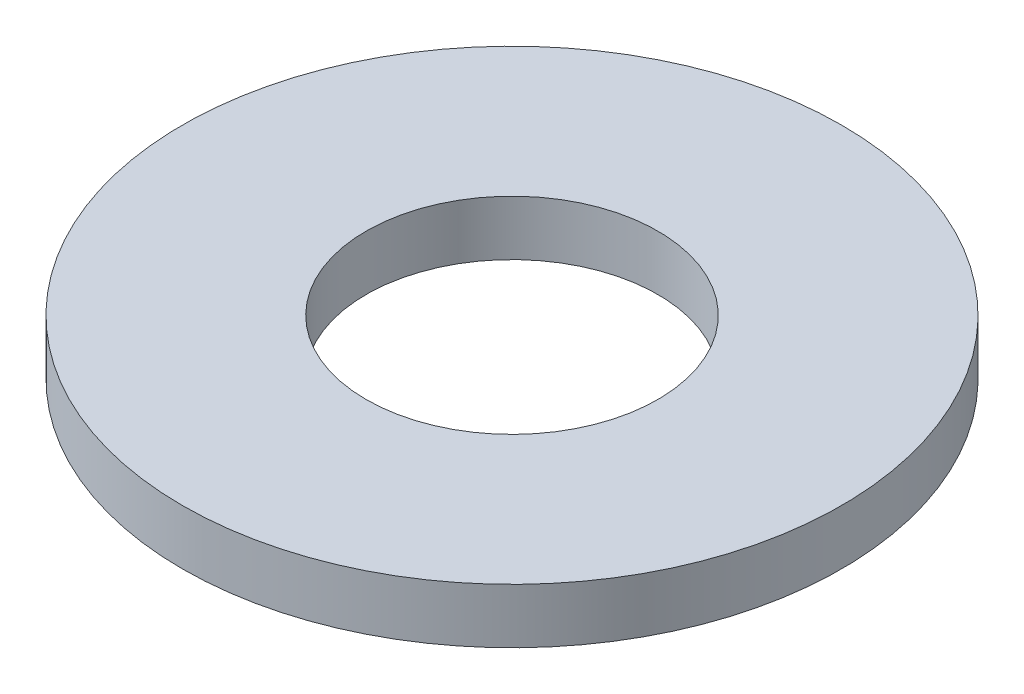
SolidWorks part; units mm, degrees
ref_plane "Front Plane" through (0, 0, 0) normal (0, 0, 1) x (1, 0, 0)
ref_plane "Top Plane" through (0, 0, 0) normal (0, 1, 0) x (1, 0, 0)
ref_plane "Right Plane" through (0, 0, 0) normal (1, 0, 0) x (0, 0, -1)
sketch "Sketch1" plane through (0, 0, 0) normal (0, 1, 0) x (1, 0, 0)
  circle A0 centre (0, 0) radius 2.1082
  circle A1 centre (0, 0) radius 4.7625
  dimension "D1" = 9.525
  dimension "D2" = 4.2164
extrude "Boss-Extrude1" add sketch "Sketch1" along normal blind 0.7937
